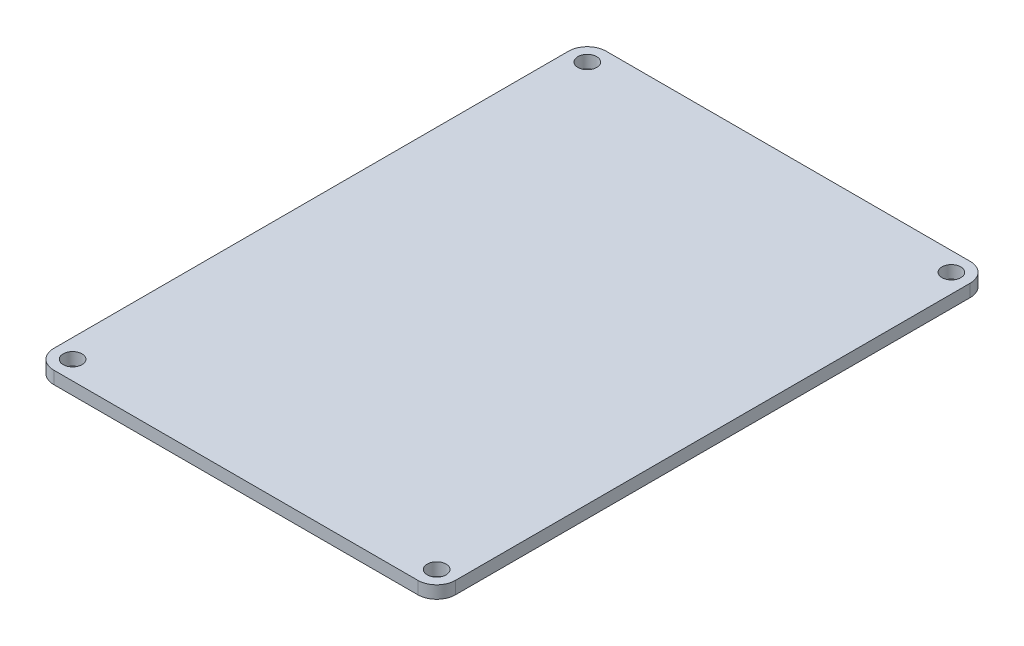
SolidWorks part; units mm, degrees
ref_plane "Front Plane" through (0, 0, 0) normal (0, 0, 1) x (1, 0, 0)
ref_plane "Top Plane" through (0, 0, 0) normal (0, 1, 0) x (1, 0, 0)
ref_plane "Right Plane" through (0, 0, 0) normal (1, 0, 0) x (0, 0, -1)
sketch "Sketch1" plane through (0, 0, 0) normal (0, 1, 0) x (1, 0, 0)
  line L1 (-32, -44) -> (32, -44)
  line L2 (-32, -44) -> (-32, 44)
  line L3 (-32, 44) -> (32, 44)
  line L4 (32, -44) -> (32, 44)
  line L5 (-32, -44) -> (32, 44) construction
  line L6 (-32, 44) -> (32, -44) construction
  point P0 (0, 0)
  dimension "D1" = 64
  dimension "D2" = 88
extrude "Boss-Extrude1" add sketch "Sketch1" along normal mid plane 2
fillet "Fillet1" radius 3 4 edges at (-32, 0, -44) (32, 0, -44) (-32, 0, 44) (32, 0, 44)
sketch "Sketch2" plane through (0, 1, 0) normal (0, 1, 0) x (1, 0, 0)
  line L1 (29, -41) -> (-29, -41) construction
  line L2 (29, -41) -> (29, 41) construction
  line L3 (29, 41) -> (-29, 41) construction
  line L4 (-29, -41) -> (-29, 41) construction
  line L5 (29, -41) -> (-29, 41) construction
  line L6 (29, 41) -> (-29, -41) construction
  circle A0 centre (-29, 41) radius 1.5
  point P0 (0, 0)
  dimension "D3" = 3
  dimension "D1" = 58
  dimension "D2" = 82
extrude "Cut-Extrude1" cut sketch "Sketch2" against normal through all both and the other way through all
mirror "Mirror1" about plane through (0, 0, 0) normal (1, 0, 0) of "Cut-Extrude1"
mirror "Mirror2" about plane through (0, 0, 0) normal (0, 0, 1) of "Mirror1", "Cut-Extrude1"
